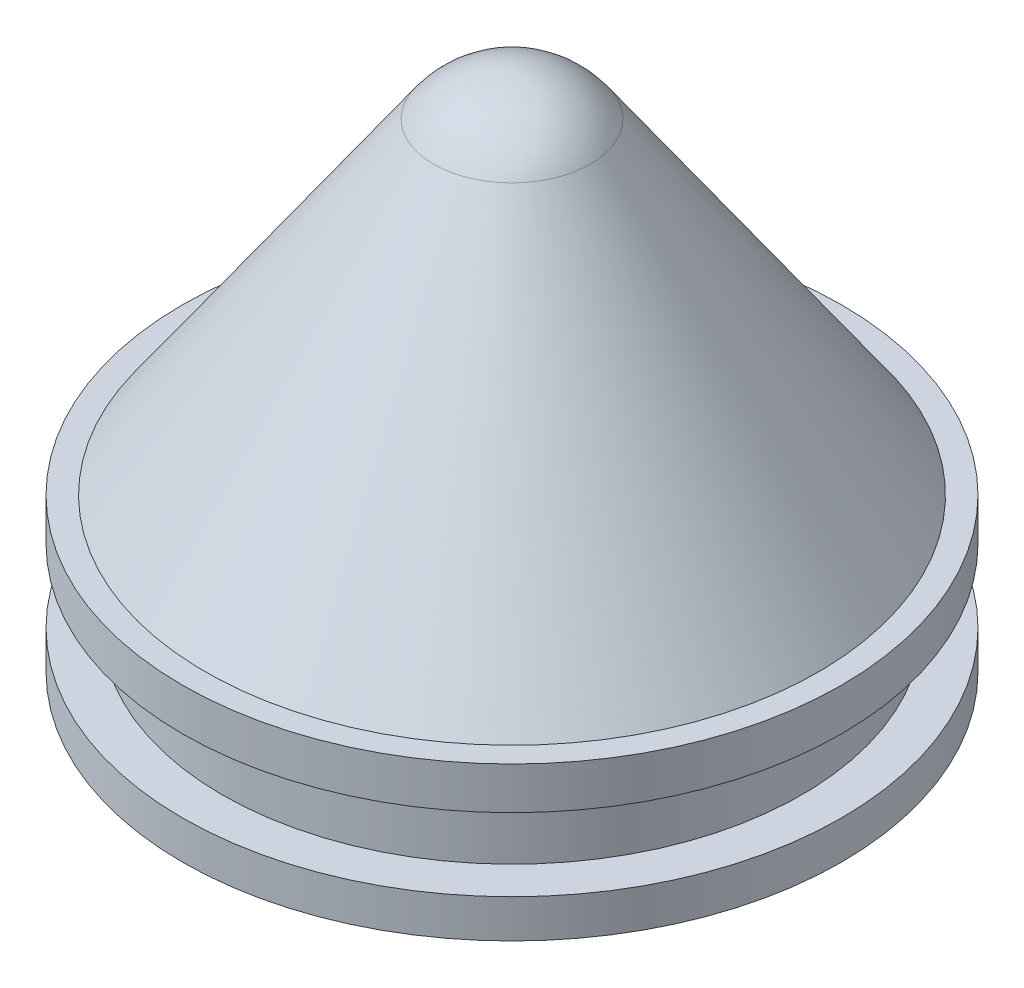
SolidWorks part; units mm, degrees
material "AISI 304"
ref_plane "Front Plane" through (0, 0, 0) normal (0, 0, 1) x (1, 0, 0)
ref_plane "Top Plane" through (0, 0, 0) normal (0, 1, 0) x (1, 0, 0)
ref_plane "Right Plane" through (0, 0, 0) normal (1, 0, 0) x (0, 0, -1)
ref_axis "Axis1" through (0, 21.1841, 0) along (0, -1, 0)
sketch "Sketch1" plane through (0, 0, 0) normal (0, 1, 0) x (1, 0, 0)
  circle A0 centre (0, 0) radius 10.922
  dimension "D1" = 21.844
extrude "Boss-Extrude1" add sketch "Sketch1" along normal blind 5.08
sketch "Sketch4" plane through (0, 0, 0) normal (0, 0, 1) x (1, 0, 0)
  line L0 (10.922, 5.08) -> (-10.922, 5.08) construction
  line L1 (9.6012, 3.683) -> (12.0142, 3.683)
  line L2 (9.6012, 3.683) -> (9.6012, 1.27)
  line L3 (9.6012, 1.27) -> (12.0142, 1.27)
  line L4 (12.0142, 3.683) -> (12.0142, 1.27)
  line L5 (10.922, 9.7299) -> (10.922, 50009.7299) construction
  line L6 (0, 0) -> (0, 50000) construction
  line L7 (0, 0) -> (-50000, 0) construction
  point P11 (10.922, 5.08)
  dimension "D1" = 1.27
  dimension "D2" = 9.6012
  dimension "D3" = 2.413
revolve "Cut-Revolve1" cut sketch "Sketch4" angle 360 about L6
sketch "Sketch5" plane through (0, 0, 0) normal (0, 0, 1) x (1, 0, 0)
  line L0 (10.16, 5.08) -> (2.6008, 15.8756)
  line L1 (0, 17.2295) -> (0, 5.08)
  line L2 (0, 5.08) -> (10.16, 5.08)
  line L3 (10.922, 5.08) -> (-10.922, 5.08) construction
  line L4 (0, 17.2295) -> (-1.8206, 17.2295) construction
  arc A0 (0, 17.2295) -> (2.6008, 15.8756) centre (0, 14.0545) cw
  dimension "D3" = 3.175
  dimension "D1" = 10.16
  dimension "D2" = 55
revolve "Revolve1" add sketch "Sketch5" angle 360 about axis through (0, 21.1841, 0) along (0, -1, 0)
